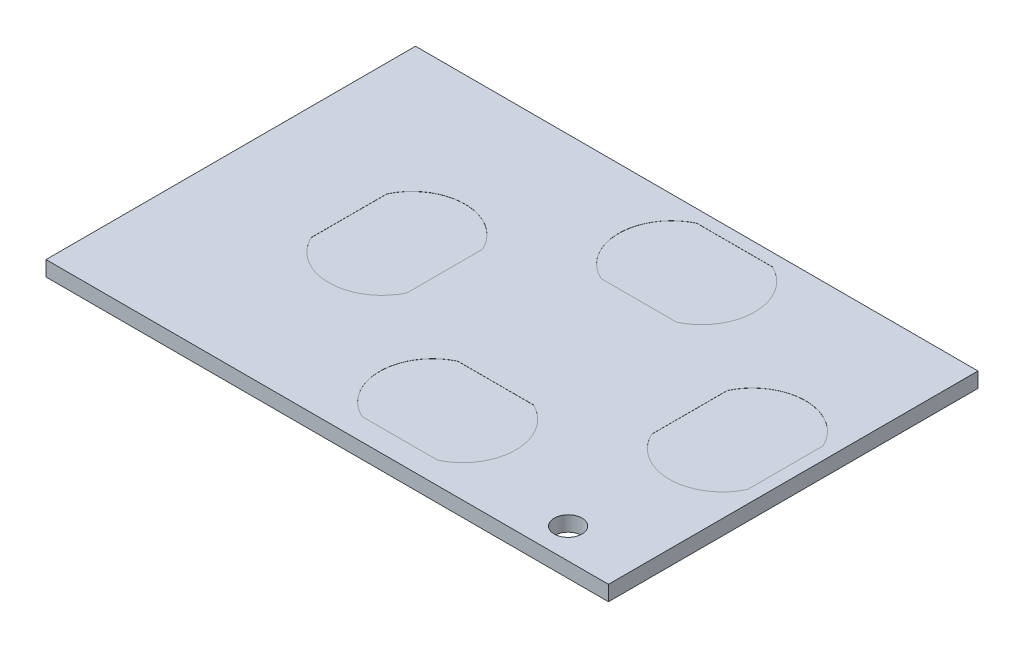
SolidWorks part; units mm, degrees
ref_plane "Plan de face" through (0, 0, 0) normal (0, 0, 1) x (1, 0, 0)
ref_plane "Plan de dessus" through (0, 0, 0) normal (0, 1, 0) x (1, 0, 0)
ref_plane "Plan de droite" through (0, 0, 0) normal (1, 0, 0) x (0, 0, -1)
sketch "Esquisse1" plane through (0, 0, 0) normal (0, 1, 0) x (1, 0, 0)
  line L0 (-22.3, 14.65) -> (22.3, 14.65)
  line L1 (22.3, 14.65) -> (22.3, -14.65)
  line L2 (22.3, -14.65) -> (-22.3, -14.65)
  line L3 (-22.3, -14.65) -> (-22.3, 14.65)
  line L4 (-22.3, 14.65) -> (22.3, -14.65) construction
  line L5 (-22.3, -14.65) -> (22.3, 14.65) construction
  circle A0 centre (16.7, -12.25) radius 1.1
  point P2 (0, 0)
  dimension "D4" = 2.2
  dimension "D1" = 29.3
  dimension "D2" = 44.6
  dimension "D3" = 44.6
extrude "Boss.-Extru.2" add sketch "Esquisse1" along normal blind 1.2
sketch "Esquisse7" plane through (0, 1.2, 0) normal (0, 1, 0) x (1, 0, 0)
  line L0 (1, 13.65) -> (7, 13.65)
  line L1 (7, 6.05) -> (1, 6.05)
  line L2 (1, -5.3) -> (7, -5.3)
  line L3 (7, -12.9) -> (1, -12.9)
  line L4 (-13.3, 3.375) -> (-13.3, -2.625)
  line L5 (-5.7, -2.625) -> (-5.7, 3.375)
  line L6 (4, 6.05) -> (4, -5.3) construction
  line L7 (13.7, 3.375) -> (13.7, -2.625)
  line L8 (21.3, -2.625) -> (21.3, 3.375)
  line L9 (22.3, 14.65) -> (-22.3, 14.65) construction
  line L10 (-22.3, -14.65) -> (22.3, -14.65) construction
  line L11 (-22.3, 14.65) -> (-22.3, -14.65) construction
  arc A1 (7, 13.65) -> (7, 6.05) centre (5.1917, 9.85) cw
  arc A2 (1, 13.65) -> (1, 6.05) centre (2.8083, 9.85) ccw
  arc A3 (7, -5.3) -> (7, -12.9) centre (5.1917, -9.1) cw
  arc A4 (1, -5.3) -> (1, -12.9) centre (2.8083, -9.1) ccw
  arc A5 (-13.3, -2.625) -> (-5.7, -2.625) centre (-9.5, -0.8167) ccw
  arc A6 (-13.3, 3.375) -> (-5.7, 3.375) centre (-9.5, 1.5667) cw
  arc A7 (13.7, -2.625) -> (21.3, -2.625) centre (17.5, -0.8167) ccw
  arc A8 (13.7, 3.375) -> (21.3, 3.375) centre (17.5, 1.5667) cw
  point P10 (-1.4, 9.85)
  point P11 (9.4, 9.85)
  point P24 (-9.5, -5.025)
  point P25 (-9.5, 5.775)
  point P26 (4, 0.375)
  point P27 (-5.7, 0.375)
  point P36 (17.5, -5.025)
  point P37 (17.5, 5.775)
  point P38 (13.7, 0.375)
  dimension "D1" = 7.6
  dimension "D2" = 7.6
  dimension "D3" = 7.6
  dimension "D4" = 10.8
  dimension "D5" = 6
  dimension "D6" = 7.6
  dimension "D7" = 9.7
  dimension "D8" = 1
  dimension "D9" = 1.75
  dimension "D10" = 9.7
  dimension "D11" = 9
  dimension "D12" = 6
  dimension "D13" = 6
  dimension "D14" = 10.8
  dimension "D15" = 10.8
extrude "Enlèv. mat.-Extru.1" cut sketch "Esquisse7" against normal blind 0.01
sketch "Esquisse8" plane through (0, 1.2, 0) normal (0, 1, 0) x (1, 0, 0)
  line L0 (1, 13.65) -> (7, 6.05) construction
  line L1 (7, 6.05) -> (1, 6.05) construction
  line L2 (1, 6.05) -> (7, 13.65) construction
  line L3 (-13.3, 3.375) -> (-5.7, -2.625) construction
  line L4 (-13.3, -2.625) -> (-5.7, 3.375) construction
  line L5 (1, -5.3) -> (7, -12.9) construction
  line L6 (1, -12.9) -> (7, -5.3) construction
  line L7 (13.7, 3.375) -> (21.3, -2.625) construction
  line L8 (13.7, -2.625) -> (21.3, 3.375) construction
  point P4 (4, 9.85)
  point P17 (-9.5, 0.375)
  point P26 (4, -9.1)
  point P35 (17.5, 0.375)
